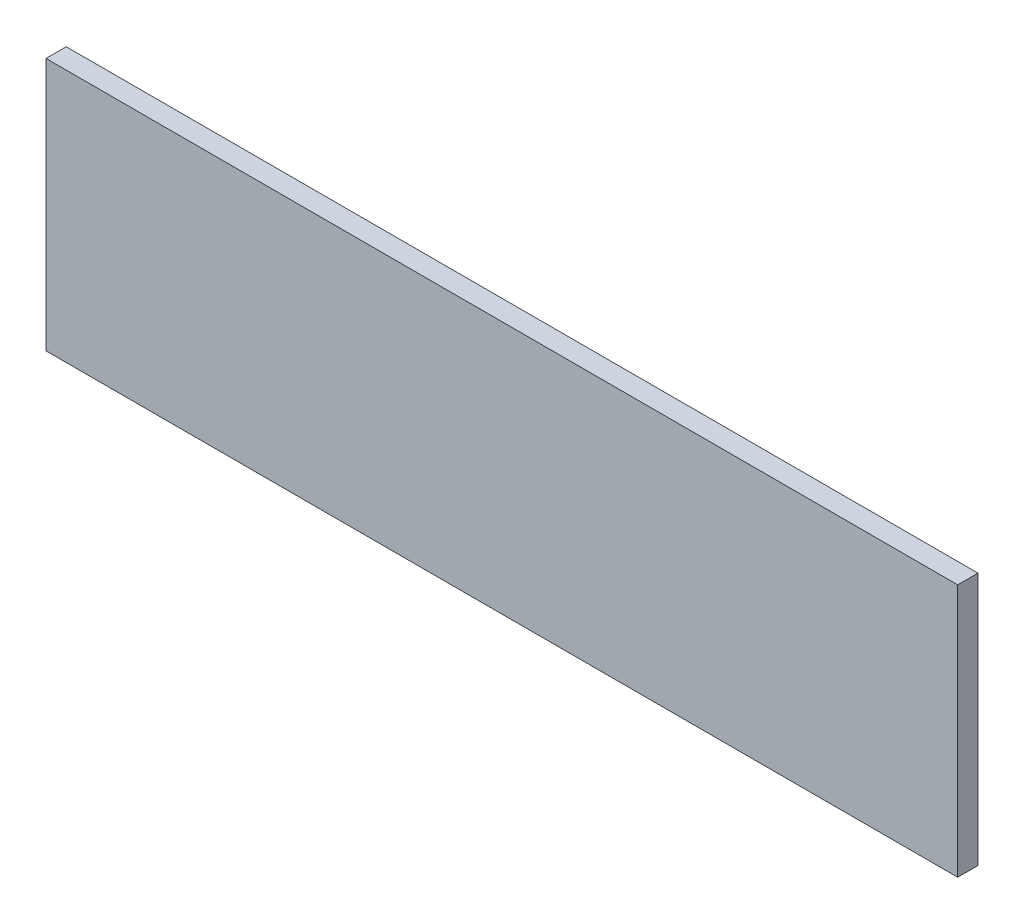
SolidWorks part; units mm, degrees
ref_plane "Front Plane" through (0, 0, 0) normal (0, 0, 1) x (1, 0, 0)
ref_plane "Top Plane" through (0, 0, 0) normal (0, 1, 0) x (1, 0, 0)
ref_plane "Right Plane" through (0, 0, 0) normal (1, 0, 0) x (0, 0, -1)
sketch "Sketch1" plane through (0, 0, 0) normal (0, 0, 1) x (1, 0, 0)
  line L1 (45, -12.5) -> (-45, -12.5)
  line L2 (45, -12.5) -> (45, 12.5)
  line L3 (45, 12.5) -> (-45, 12.5)
  line L4 (-45, -12.5) -> (-45, 12.5)
  line L5 (45, -12.5) -> (-45, 12.5) construction
  line L6 (45, 12.5) -> (-45, -12.5) construction
  point P0 (0, 0)
  dimension "D1" = 25
  dimension "D2" = 90
extrude "Boss-Extrude1" add sketch "Sketch1" along normal blind 2
